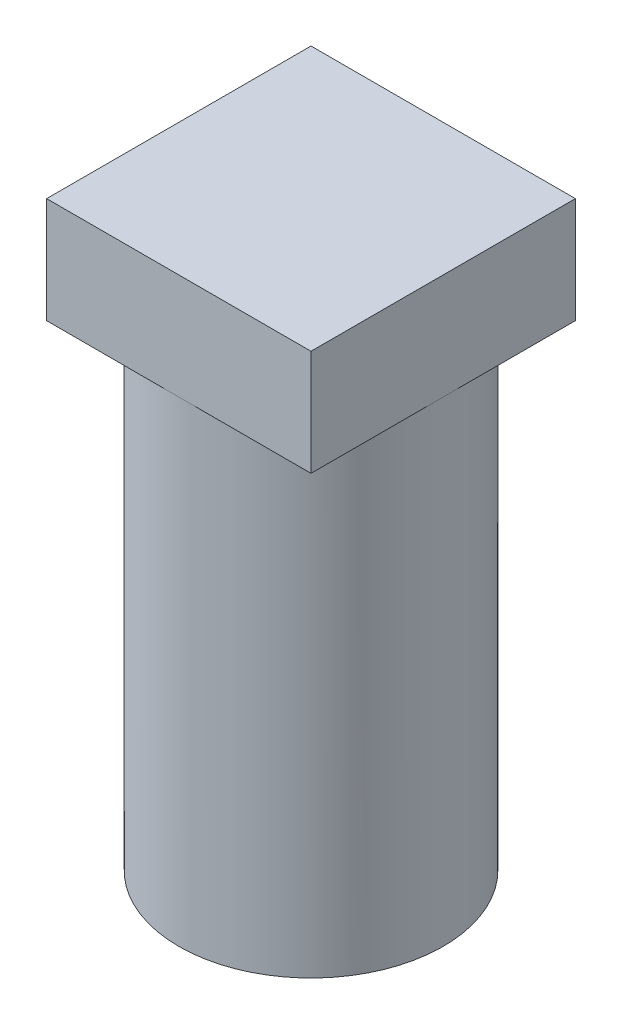
SolidWorks part; units mm, degrees
ref_plane "Front Plane" through (0, 0, 0) normal (0, 0, 1) x (1, 0, 0)
ref_plane "Top Plane" through (0, 0, 0) normal (0, 1, 0) x (1, 0, 0)
ref_plane "Right Plane" through (0, 0, 0) normal (1, 0, 0) x (0, 0, -1)
sketch "Sketch1" plane through (0, 0, 0) normal (0, 1, 0) x (1, 0, 0)
  circle A0 centre (0, 0) radius 2.5
extrude "Boss-Extrude1" add sketch "Sketch1" along normal blind 9
sketch "Sketch2" plane through (0, 9, 0) normal (0, 1, 0) x (1, 0, 0)
  line L1 (-2.5, 2.5) -> (2.5, 2.5)
  line L2 (-2.5, 2.5) -> (-2.5, -2.5)
  line L3 (-2.5, -2.5) -> (2.5, -2.5)
  line L4 (2.5, 2.5) -> (2.5, -2.5)
  line L5 (-2.5, 2.5) -> (2.5, -2.5) construction
  line L6 (-2.5, -2.5) -> (2.5, 2.5) construction
  point P0 (0, 0)
  dimension "D1" = 5
  dimension "D2" = 5
extrude "Boss-Extrude2" add sketch "Sketch2" along normal blind 2
scale "Scale1" scale about centroid uniform scaling yes scale factor 2
sketch "Sketch4" plane through (0, -5.713, 0) normal (0, -1, 0) x (1, 0, 0)
  circle A0 centre (0, 0) radius 5
  dimension "D1" = 10
